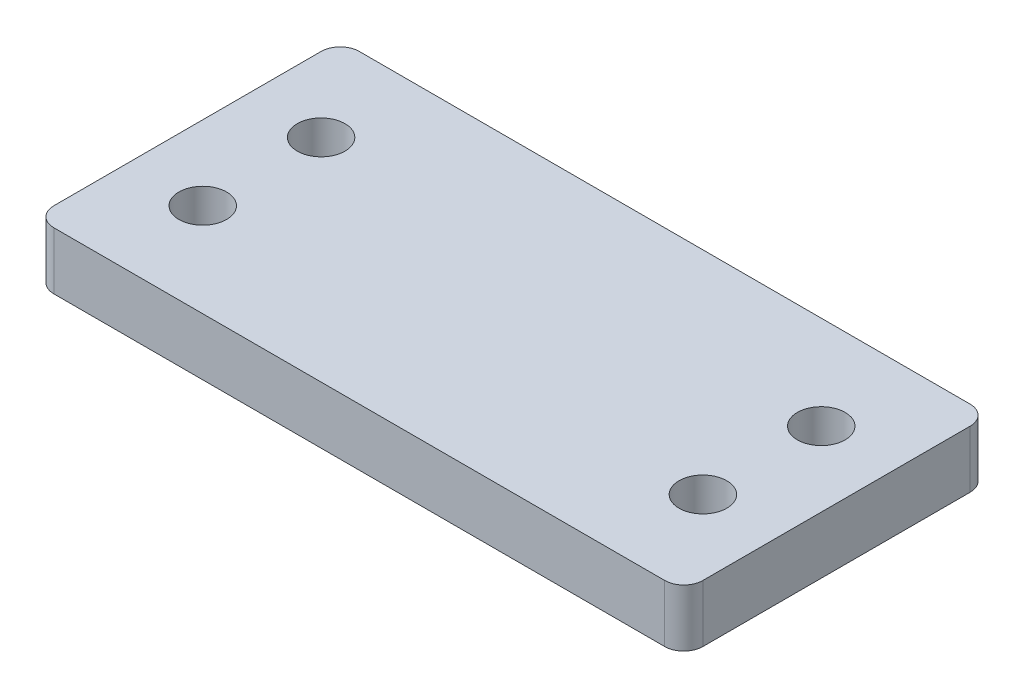
SolidWorks part; units mm, degrees
ref_plane "前视基准面" through (0, 0, 0) normal (0, 0, 1) x (1, 0, 0)
ref_plane "上视基准面" through (0, 0, 0) normal (0, 1, 0) x (1, 0, 0)
ref_plane "右视基准面" through (0, 0, 0) normal (1, 0, 0) x (0, 0, -1)
sketch "草图3" plane through (0, 0, 0) normal (0, 1, 0) x (1, 0, 0)
  line L0 (-13.1, 3.1) -> (13.1, -3.1) construction
  line L1 (13.1, 3.1) -> (-13.1, -3.1) construction
  line L2 (-17, 8) -> (17, -8) construction
  line L3 (-17, 8) -> (17, 8)
  line L4 (-17, 8) -> (-17, -8)
  line L5 (-17, -8) -> (17, -8)
  line L6 (17, 8) -> (17, -8)
  line L7 (17, 8) -> (-17, -8) construction
  circle A12 centre (-13.1, 3.1) radius 2.55 construction
  arc A13 (-13.1, -4.35) -> (-13.1, -1.85) centre (-13.1, -3.1) ccw
  arc A14 (-13.1, -1.85) -> (-13.1, -4.35) centre (-13.1, -3.1) ccw
  circle A15 centre (-13.1, -3.1) radius 2.55 construction
  arc A16 (13.1, -4.35) -> (13.1, -1.85) centre (13.1, -3.1) ccw
  arc A17 (13.1, -1.85) -> (13.1, -4.35) centre (13.1, -3.1) ccw
  circle A18 centre (13.1, -3.1) radius 2.55 construction
  circle A19 centre (13.1, 3.1) radius 2.55 construction
  arc A20 (13.1, 4.35) -> (13.1, 1.85) centre (13.1, 3.1) ccw
  arc A21 (13.1, 1.85) -> (13.1, 4.35) centre (13.1, 3.1) ccw
  arc A22 (-13.1, 1.85) -> (-13.1, 4.35) centre (-13.1, 3.1) ccw
  arc A23 (-13.1, 4.35) -> (-13.1, 1.85) centre (-13.1, 3.1) ccw
extrude "凸台-拉伸3" add sketch "草图3" along normal blind 3
fillet "圆角1" radius 1 4 edges at (-17, 1.5, -8) (-17, 1.5, 8) (17, 1.5, -8) (17, 1.5, 8)
